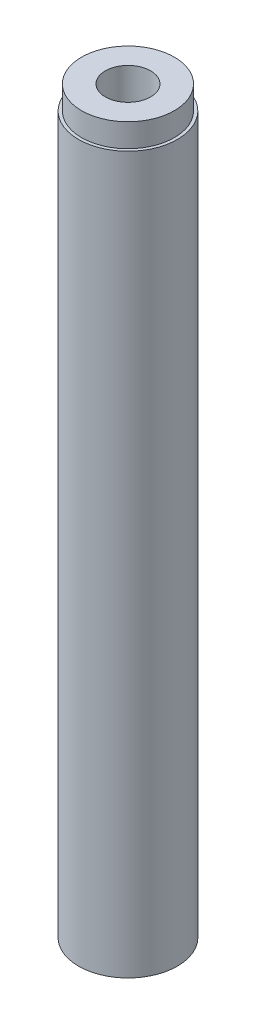
SolidWorks part; units mm, degrees
ref_plane "Front Plane" through (0, 0, 0) normal (0, 0, 1) x (1, 0, 0)
ref_plane "Top Plane" through (0, 0, 0) normal (0, 1, 0) x (1, 0, 0)
ref_plane "Right Plane" through (0, 0, 0) normal (1, 0, 0) x (0, 0, -1)
sketch "Sketch1" plane through (0, 0, 0) normal (0, 1, 0) x (1, 0, 0)
  circle A0 centre (0, 0) radius 6.55
  circle A1 centre (0, 0) radius 3
  dimension "D1" = 13.1
  dimension "D2" = 6
extrude "Boss-Extrude1" add sketch "Sketch1" along normal blind 98
sketch "Sketch2" plane through (0, 98, 0) normal (0, 1, 0) x (1, 0, 0)
  circle A0 centre (0, 0) radius 6.15
  circle A1 centre (0, 0) radius 6.55 construction
  circle A2 centre (0, 0) radius 6.55
  dimension "D1" = 12.3
extrude "Cut-Extrude1" cut sketch "Sketch2" against normal blind 3.1 contours A2 | A0
